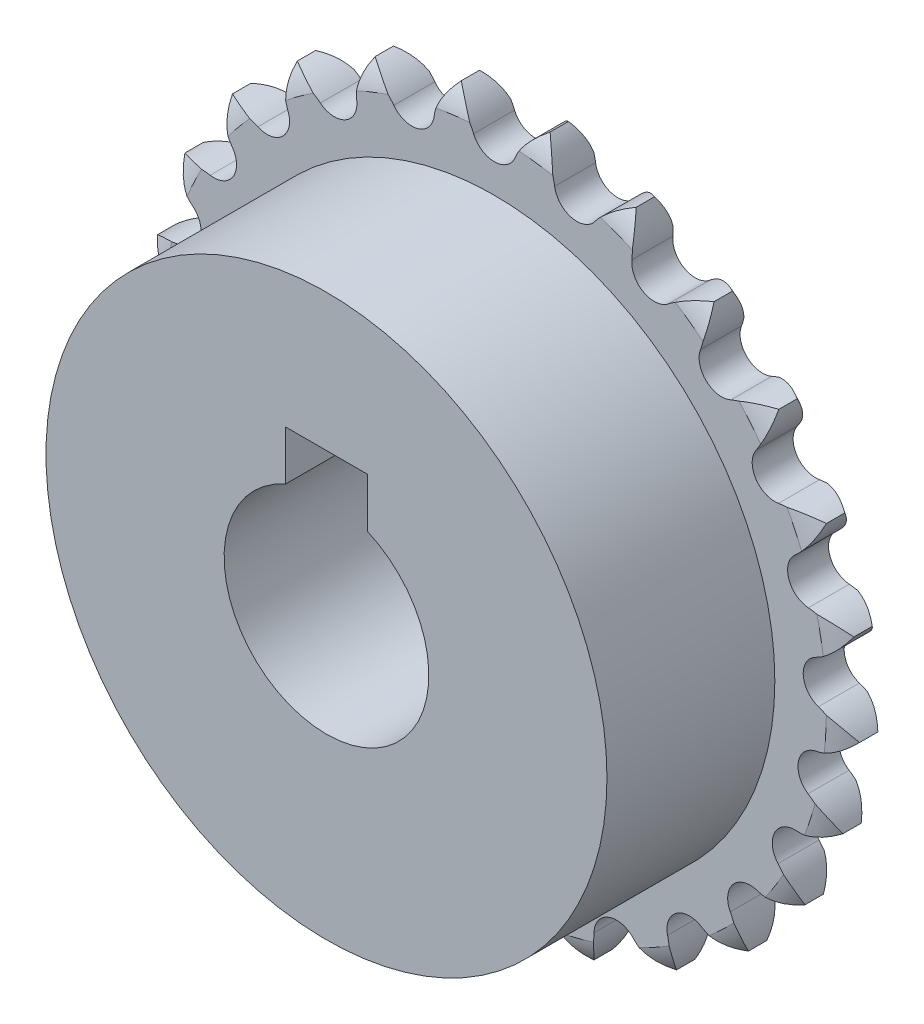
SolidWorks part; units mm, degrees
material "Acero aleado fundido"
ref_plane "Alzado" through (0, 0, 0) normal (0, 0, 1) x (1, 0, 0)
ref_plane "Planta" through (0, 0, 0) normal (0, 1, 0) x (1, 0, 0)
ref_plane "Vista lateral" through (0, 0, 0) normal (1, 0, 0) x (0, 0, -1)
sketch "Croquis1" plane through (0, 0, 0) normal (0, 0, 1) x (1, 0, 0)
  line L0 (0, 0) -> (0, 26.035) construction
  circle A0 centre (0, 0) radius 26.035 construction
  circle A1 centre (0, 0) radius 24.325 construction
  circle A2 centre (0, 0) radius 22.67 construction
  arc A5 (-1.5231, 23.6905) -> (1.5231, 23.6905) centre (0, 24.325) ccw
  arc A6 (3.333, 25.8208) -> (1.5231, 23.6905) centre (5.7579, 21.9266) ccw
  arc A7 (10.0543, 20.3185) -> (10.3445, 22.0158) centre (5.7579, 21.9266) ccw
  arc A8 (-3.333, 25.8208) -> (-1.5231, 23.6905) centre (-5.7579, 21.9266) cw
  arc A9 (3.1931, 25.8385) -> (4.4163, 23.3251) centre (-0.1241, 22.6697) cw
  arc A10 (4.4163, 23.3251) -> (7.3669, 22.5675) centre (6.0494, 23.5608) ccw
  arc A11 (9.6497, 24.1807) -> (7.3669, 22.5675) centre (11.0299, 19.8058) ccw
  arc A12 (9.5185, 24.2326) -> (10.0783, 21.494) centre (5.5175, 21.9883) cw
  arc A13 (10.0783, 21.494) -> (12.7477, 20.0264) centre (11.7187, 21.3162) ccw
  arc A14 (15.36, 21.0212) -> (12.7477, 20.0264) centre (15.6089, 16.4405) ccw
  arc A15 (15.2459, 21.1041) -> (15.107, 18.3123) centre (10.8124, 19.9254) cw
  arc A16 (15.107, 18.3123) -> (17.3276, 16.227) centre (16.6516, 17.7322) ccw
  arc A17 (20.1052, 16.5409) -> (17.3276, 16.227) centre (19.2071, 12.0422) ccw
  arc A18 (20.0153, 16.6496) -> (19.1864, 13.9801) centre (15.428, 16.6104) cw
  arc A19 (19.1864, 13.9801) -> (20.8187, 11.408) centre (20.5383, 13.034) ccw
  arc A20 (23.5871, 11.0213) -> (20.8187, 11.408) centre (21.5985, 6.8873) ccw
  arc A21 (23.5271, 11.1489) -> (22.0604, 8.7694) centre (19.0741, 12.2518) cw
  arc A22 (22.0604, 8.7694) -> (23.0017, 5.8722) centre (23.1344, 7.5168) ccw
  arc A23 (25.587, 4.8092) -> (23.0017, 5.8722) centre (22.6327, 1.2996) ccw
  arc A24 (25.5605, 4.9477) -> (23.5482, 3.0077) centre (21.5218, 7.1233) cw
  arc A25 (23.5482, 3.0077) -> (23.7394, -0.0326) centre (24.277, 1.5274) ccw
  arc A26 (25.9791, -1.7051) -> (23.7394, -0.0326) centre (22.2449, -4.3698) ccw
  arc A27 (25.988, -1.5644) -> (23.5563, -2.943) centre (22.6171, 1.5473) cw
  arc A28 (23.5563, -2.943) -> (22.9855, -5.9353) centre (23.8941, -4.5581) ccw
  arc A29 (24.7389, -8.1123) -> (22.9855, -5.9353) centre (20.4593, -9.7646) ccw
  arc A30 (24.7825, -7.9782) -> (22.0844, -8.7088) centre (22.2914, -4.126) cw
  arc A31 (22.0844, -8.7088) -> (20.7873, -11.4651) centre (22.0099, -10.3571) ccw
  arc A32 (21.9442, -14.0097) -> (20.7873, -11.4651) centre (17.3882, -14.5458) ccw
  arc A33 (22.0198, -13.8907) -> (19.2248, -13.9273) centre (20.565, -9.54) cw
  arc A34 (19.2248, -13.9273) -> (17.283, -16.2745) centre (18.7427, -15.5053) ccw
  arc A35 (17.7707, -19.0269) -> (17.283, -16.2745) centre (13.2245, -18.4131) ccw
  arc A36 (17.8735, -18.9303) -> (15.1572, -18.2708) centre (17.5464, -14.3546) cw
  arc A37 (15.1572, -18.2708) -> (12.6927, -20.0613) centre (14.2979, -19.6793) ccw
  arc A38 (12.4806, -22.8485) -> (12.6927, -20.0613) centre (8.2299, -21.1234) ccw
  arc A39 (12.6042, -22.7806) -> (10.1373, -21.4662) centre (13.4253, -18.2672) cw
  arc A40 (10.1373, -21.4662) -> (7.3049, -22.5876) centre (8.9546, -22.6168) ccw
  arc A41 (6.4063, -25.2345) -> (7.3049, -22.5876) centre (2.7181, -22.5065) ccw
  arc A42 (6.5429, -25.1994) -> (4.4803, -23.3128) centre (8.4606, -21.032) cw
  arc A43 (4.4803, -23.3128) -> (1.4581, -23.6946) centre (3.0487, -24.1332) ccw
  arc A44 (-0.0705, -26.0349) -> (1.4581, -23.6946) centre (-2.9644, -22.4753) ccw
  arc A45 (0.0705, -26.0349) -> (-1.4581, -23.6946) centre (2.9644, -22.4753) cw
  arc A46 (-1.4581, -23.6946) -> (-4.4803, -23.3128) centre (-3.0487, -24.1332) ccw
  arc A47 (-6.5429, -25.1994) -> (-4.4803, -23.3128) centre (-8.4606, -21.032) ccw
  arc A48 (-6.4063, -25.2345) -> (-7.3049, -22.5876) centre (-2.7181, -22.5065) cw
  arc A49 (-7.3049, -22.5876) -> (-10.1373, -21.4662) centre (-8.9546, -22.6168) ccw
  arc A50 (-12.6042, -22.7806) -> (-10.1373, -21.4662) centre (-13.4253, -18.2672) ccw
  arc A51 (-12.4806, -22.8485) -> (-12.6927, -20.0613) centre (-8.2299, -21.1234) cw
  arc A52 (-12.6927, -20.0613) -> (-15.1572, -18.2708) centre (-14.2979, -19.6793) ccw
  arc A53 (-17.8735, -18.9303) -> (-15.1572, -18.2708) centre (-17.5464, -14.3546) ccw
  arc A54 (-17.7707, -19.0269) -> (-17.283, -16.2745) centre (-13.2245, -18.4131) cw
  arc A55 (-17.283, -16.2745) -> (-19.2248, -13.9273) centre (-18.7427, -15.5053) ccw
  arc A56 (-22.0198, -13.8907) -> (-19.2248, -13.9273) centre (-20.565, -9.54) ccw
  arc A57 (-21.9442, -14.0097) -> (-20.7873, -11.4651) centre (-17.3882, -14.5458) cw
  arc A58 (-20.7873, -11.4651) -> (-22.0844, -8.7088) centre (-22.0099, -10.3571) ccw
  arc A59 (-24.7825, -7.9782) -> (-22.0844, -8.7088) centre (-22.2914, -4.126) ccw
  arc A60 (-24.7389, -8.1123) -> (-22.9855, -5.9353) centre (-20.4593, -9.7646) cw
  arc A61 (-22.9855, -5.9353) -> (-23.5563, -2.943) centre (-23.8941, -4.5581) ccw
  arc A62 (-25.988, -1.5644) -> (-23.5563, -2.943) centre (-22.6171, 1.5473) ccw
  arc A63 (-25.9791, -1.7051) -> (-23.7394, -0.0326) centre (-22.2449, -4.3698) cw
  arc A64 (-23.7394, -0.0326) -> (-23.5482, 3.0077) centre (-24.277, 1.5274) ccw
  arc A65 (-25.5605, 4.9477) -> (-23.5482, 3.0077) centre (-21.5218, 7.1233) ccw
  arc A66 (-25.587, 4.8092) -> (-23.0017, 5.8722) centre (-22.6327, 1.2996) cw
  arc A67 (-23.0017, 5.8722) -> (-22.0604, 8.7694) centre (-23.1344, 7.5168) ccw
  arc A68 (-23.5271, 11.1489) -> (-22.0604, 8.7694) centre (-19.0741, 12.2518) ccw
  arc A69 (-23.5871, 11.0213) -> (-20.8187, 11.408) centre (-21.5985, 6.8873) cw
  arc A70 (-20.8187, 11.408) -> (-19.1864, 13.9801) centre (-20.5383, 13.034) ccw
  arc A71 (-20.0153, 16.6496) -> (-19.1864, 13.9801) centre (-15.428, 16.6104) ccw
  arc A72 (-20.1052, 16.5409) -> (-17.3276, 16.227) centre (-19.2071, 12.0422) cw
  arc A73 (-17.3276, 16.227) -> (-15.107, 18.3123) centre (-16.6516, 17.7322) ccw
  arc A74 (-15.2459, 21.1041) -> (-15.107, 18.3123) centre (-10.8124, 19.9254) ccw
  arc A75 (-15.36, 21.0212) -> (-12.7477, 20.0264) centre (-15.6089, 16.4405) cw
  arc A76 (-12.7477, 20.0264) -> (-10.0783, 21.494) centre (-11.7187, 21.3162) ccw
  arc A77 (-9.5185, 24.2326) -> (-10.0783, 21.494) centre (-5.5175, 21.9883) ccw
  arc A78 (-9.6497, 24.1807) -> (-7.3669, 22.5675) centre (-11.0299, 19.8058) cw
  arc A79 (-7.3669, 22.5675) -> (-4.4163, 23.3251) centre (-6.0494, 23.5608) ccw
  arc A80 (-3.1931, 25.8385) -> (-4.4163, 23.3251) centre (0.1241, 22.6697) ccw
  circle A81 centre (0, 0) radius 7.5
  point P186 (0, 0)
  dimension "D1" = 52.07
  dimension "D2" = 48.65
  dimension "D3" = 45.34
  dimension "D4" = 3.3
  dimension "D7" = 15
  dimension "D6" = 25
extrude "Saliente-Extruir1" add sketch "Croquis1" along normal mid plane 3 contours A8 A80 A79 A78 A77 A76 A75 A74 A73 A72 A71 A70 A69 A68 A67 A66 A65 A64 A63 A62 A61 A60 A59 A58 A57 A56 A55 A54 A53 A52 A51 A50 A49 A48 A47 A46 A45 A44 A43 A42 A41 A40 A39 A38 A37 A36 A35 A34 A33 A32 A31
sketch "Croquis2" plane through (0, 0, 1.5) normal (0, 0, 1) x (1, 0, 0)
  circle A0 centre (0, 0) radius 20.55
  circle A1 centre (0, 0) radius 7.5 construction
  circle A2 centre (0, 0) radius 7.5
  dimension "D1" = 41.1
extrude "Saliente-Extruir2" add sketch "Croquis2" along normal blind 12.3
sketch "Croquis3" plane through (0, 0, 13.8) normal (0, 0, 1) x (1, 0, 0)
  line L0 (0, 0) -> (0, 7.5) construction
  line L2 (-3, 10.5) -> (3, 10.5)
  line L3 (-3, 10.5) -> (-3, 4.5)
  line L4 (-3, 4.5) -> (3, 4.5)
  line L5 (3, 10.5) -> (3, 4.5)
  line L6 (-3, 10.5) -> (3, 4.5) construction
  line L7 (-3, 4.5) -> (3, 10.5) construction
  circle A1 centre (0, 0) radius 7.5 construction
  dimension "D1" = 6
  dimension "D2" = 6
extrude "Cortar-Extruir1" cut sketch "Croquis3" against normal through all
ref_axis "Eje1" through (0, 0, 79.4759) along (0, 0, -1)
sketch "Croquis4" plane through (0, 0, 0) normal (1, 0, 0) x (0, 0, -1)
  line L0 (-1.5, 25.7716) -> (1.5, 25.7716) construction
  line L2 (-3.0259, 27.2181) -> (-3.0259, 24.325)
  line L3 (-3.0259, 24.325) -> (-1.5, 24.325)
  line L5 (-3.0259, 27.2181) -> (3.0259, 24.325) construction
  line L6 (-3.0259, 24.325) -> (3.0259, 27.2181) construction
  line L7 (-1.5, 25.7716) -> (-1.5, 23.3251) construction
  line L10 (0, 27.6794) -> (0, 23.8344) construction
  line L12 (3.0259, 27.2181) -> (3.0259, 24.325)
  line L13 (3.0259, 24.325) -> (1.5, 24.325)
  line L14 (-3.0259, 27.2181) -> (3.0259, 27.2181)
  line L15 (0.38, 26.275) -> (-0.38, 26.275)
  spline S0 degree 2 poles (-1.5, 24.325) (-1.2262, 25.4886) (-0.38, 26.275) knots 0 0 0 1 1 1
  spline S1 degree 2 poles (1.5, 24.325) (1.2262, 25.4886) (0.38, 26.275) knots 0 0 0 1 1 1
  point P0 (0, 25.7716)
  dimension "D1" = 24.325
revolve "Cortar-Revolución1" cut sketch "Croquis4" angle 360 about axis through (0, 0, 79.4759) along (0, 0, -1)
